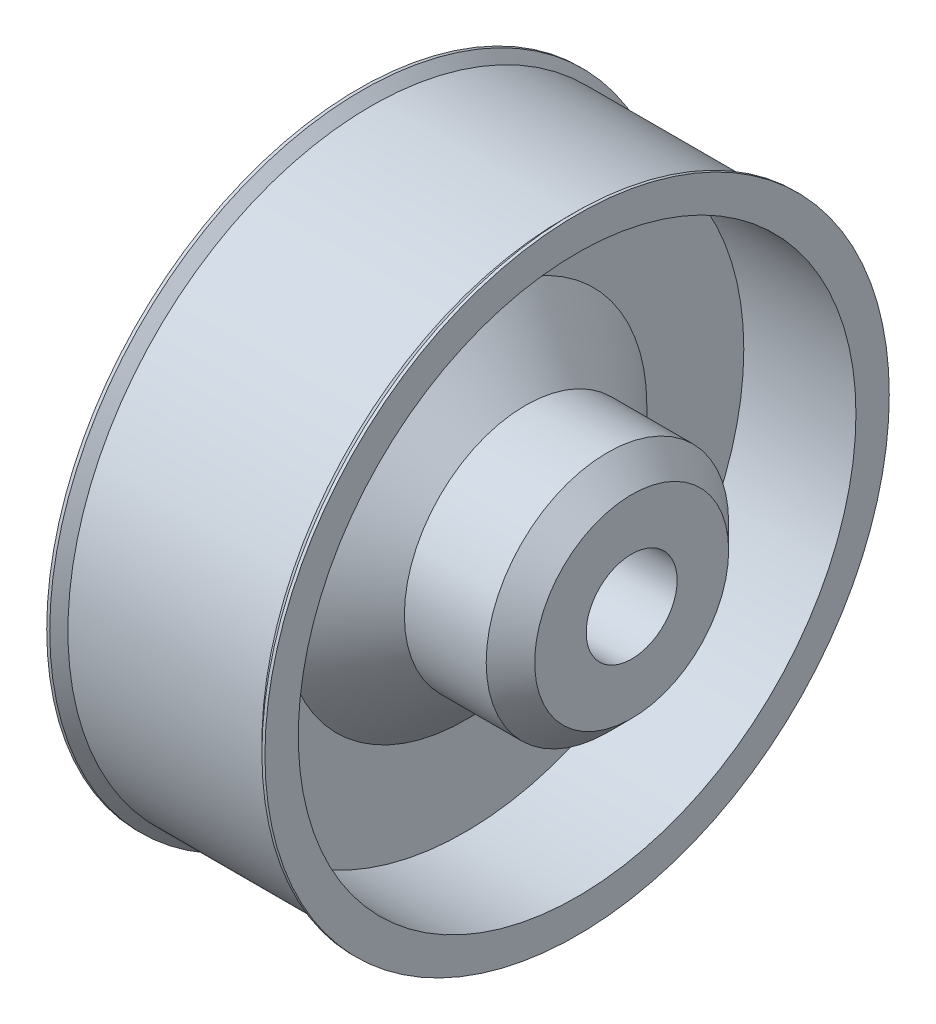
SolidWorks part; units mm, degrees
ref_plane "Front Plane" through (0, 0, 0) normal (0, 0, 1) x (1, 0, 0)
ref_plane "Top Plane" through (0, 0, 0) normal (0, 1, 0) x (1, 0, 0)
ref_plane "Right Plane" through (0, 0, 0) normal (1, 0, 0) x (0, 0, -1)
sketch "Sketch1" plane through (0, 0, 0) normal (0, 0, 1) x (1, 0, 0)
  line L0 (0, 46.0572) -> (0, 0) construction
  line L1 (0, 0) -> (-24.3874, 0) construction
  line L2 (-7.5, 6) -> (-17.5063, 3.75)
  line L3 (-17.5063, 3.75) -> (-18, 0)
  line L4 (-18, 0) -> (0, 0)
  line L5 (0, 0) -> (0, 7.5)
  line L6 (0, 7.5) -> (27.5, 7.5)
  line L7 (27.5, 7.5) -> (27.5, 16)
  line L8 (27.5, 16) -> (23.5, 20)
  line L9 (23.5, 20) -> (10, 20)
  line L10 (10, 20) -> (0, 30)
  line L11 (-7.5, 6) -> (-7.5, 12.9377)
  line L12 (-7.5, 33.0623) -> (-7.5, 43)
  line L13 (0, 30) -> (0, 46)
  line L14 (0, 46) -> (18.5, 46)
  line L15 (18.5, 46) -> (18.5, 51.5)
  line L16 (18.5, 51.5) -> (18, 51.5)
  line L17 (18, 51.5) -> (16.5, 50)
  line L18 (16.5, 50) -> (-15.5, 50)
  line L19 (-15.5, 50) -> (-17, 51.5)
  line L20 (-17, 51.5) -> (-17.5, 51.5)
  line L21 (-17.5, 51.5) -> (-17.5, 48)
  line L22 (-15.5, 46) -> (-10.5, 46)
  arc A0 (-9.6429, 15.8126) -> (-9.6429, 30.1874) centre (-7.5, 23) cw
  arc A1 (-7.5, 12.9377) -> (-9.6429, 15.8126) centre (-10.5, 12.9377) ccw
  arc A2 (-7.5, 43) -> (-10.5, 46) centre (-10.5, 43) ccw
  arc A3 (-9.6429, 30.1874) -> (-7.5, 33.0623) centre (-10.5, 33.0623) ccw
  arc A4 (-17.5, 48) -> (-15.5, 46) centre (-15.5, 48) ccw
  point P16 (25.208, 51.4755)
  point P27 (14.6356, 52.0042)
  point P28 (15.1002, 48.6002)
  point P29 (28.5118, 40.771)
  dimension "D7" = 7.5
  dimension "D22" = 3
  dimension "D23" = 2
  dimension "D1" = 18
  dimension "D2" = 82.5
  dimension "D3" = 7.5
  dimension "D4" = 3.75
  dimension "D5" = 6
  dimension "D6" = 23
  dimension "D8" = 45.5
  dimension "D9" = 20
  dimension "D10" = 7.5
  dimension "D11" = 10
  dimension "D12" = 4
  dimension "D13" = 45
  dimension "D14" = 10
  dimension "D15" = 46
  dimension "D16" = 36
  dimension "D17" = 51.5
  dimension "D18" = 0.5
  dimension "D19" = 0.5
  dimension "D20" = 32
  dimension "D21" = 2
revolve "Revolve1" add sketch "Sketch1" angle 360 about L1
sketch "Sketch2" plane through (-7.5, 0, 0) normal (-1, 0, 0) x (0, 0, 1)
  line L0 (0, 0) -> (0, 54.0831) construction
  line L2 (-1.4434, 40) -> (-2.8868, 37.5)
  line L3 (-2.8868, 37.5) -> (-1.4434, 35)
  line L4 (-1.4434, 35) -> (1.4434, 35)
  line L5 (1.4434, 35) -> (2.8868, 37.5)
  line L6 (2.8868, 37.5) -> (1.4434, 40)
  line L7 (1.4434, 40) -> (-1.4434, 40)
  circle A0 centre (0, 37.5) radius 2.5 construction
  dimension "D1" = 5
  dimension "D2" = 37.5
extrude "Boss-Extrude1" add sketch "Sketch2" along normal blind 3
pattern_circular "CirPattern1" count 8 over 360 about axis through (0, 0, 0) along (1, 0, 0) of "Boss-Extrude1"
sketch "Sketch3" plane through (-7.5, 0, 0) normal (-1, 0, 0) x (0, 0, 1)
  line L0 (0, 10) -> (0, 0) construction
  line L1 (-1.4434, 12.5) -> (-2.8868, 10)
  line L2 (-2.8868, 10) -> (-1.4434, 7.5)
  line L3 (-1.4434, 7.5) -> (1.4434, 7.5)
  line L4 (1.4434, 7.5) -> (2.8868, 10)
  line L5 (2.8868, 10) -> (1.4434, 12.5)
  line L6 (1.4434, 12.5) -> (-1.4434, 12.5)
  circle A0 centre (0, 10) radius 2.5 construction
  dimension "D1" = 5
  dimension "D2" = 10
extrude "Boss-Extrude2" add sketch "Sketch3" along normal blind 3
pattern_circular "CirPattern2" count 6 over 360 about axis through (0, 0, 0) along (1, 0, 0) of "Boss-Extrude2"
